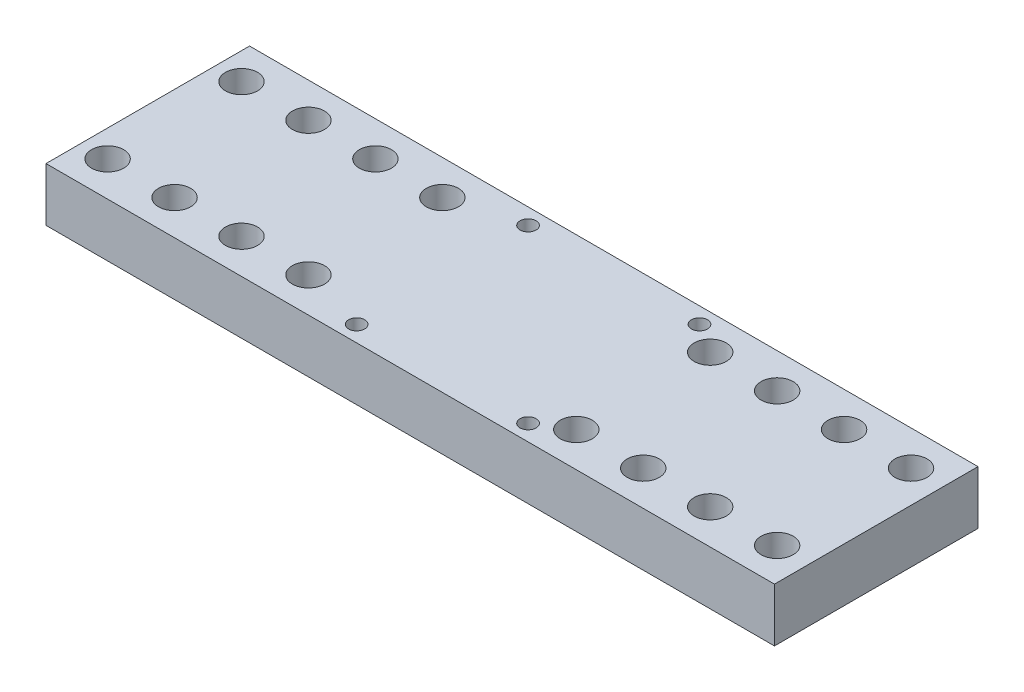
SolidWorks part; units mm, degrees
ref_plane "Front Plane" through (0, 0, 0) normal (0, 0, 1) x (1, 0, 0)
ref_plane "Top Plane" through (0, 0, 0) normal (0, 1, 0) x (1, 0, 0)
ref_plane "Right Plane" through (0, 0, 0) normal (1, 0, 0) x (0, 0, -1)
sketch "Sketch1" plane through (0, 0, 0) normal (0, 1, 0) x (1, 0, 0)
  line L1 (-70.9695, -35.3595) -> (65.0305, -35.3595)
  line L2 (-70.9695, -35.3595) -> (-70.9695, 2.6405)
  line L3 (-70.9695, 2.6405) -> (65.0305, 2.6405)
  line L4 (65.0305, -35.3595) -> (65.0305, 2.6405)
  line L5 (-15.9695, -0.3595) -> (16.0305, -0.3595) construction
  line L6 (-15.9695, -0.3595) -> (-15.9695, -32.3595) construction
  line L7 (-15.9695, -32.3595) -> (16.0305, -32.3595) construction
  line L8 (16.0305, -0.3595) -> (16.0305, -32.3595) construction
  line L9 (-65.9695, -3.8595) -> (-40.9695, -3.8595) construction
  line L10 (-65.9695, -3.8595) -> (-65.9695, -28.8595) construction
  line L11 (-65.9695, -28.8595) -> (-40.9695, -28.8595) construction
  line L12 (-40.9695, -3.8595) -> (-40.9695, -28.8595) construction
  circle A0 centre (-15.9695, -0.3595) radius 1.5
  circle A1 centre (16.0305, -0.3595) radius 1.5
  circle A2 centre (16.0305, -32.3595) radius 1.5
  circle A3 centre (-15.9695, -32.3595) radius 1.5
  circle A4 centre (-65.9695, -3.8595) radius 3
  circle A5 centre (-40.9695, -3.8595) radius 3
  circle A6 centre (-40.9695, -28.8595) radius 3
  circle A7 centre (-65.9695, -28.8595) radius 3
  circle A8 centre (-28.4695, -28.8595) radius 3
  circle A9 centre (-53.4695, -3.8595) radius 3
  circle A10 centre (-53.4695, -28.8595) radius 3
  circle A11 centre (-28.4695, -3.8595) radius 3
  circle A12 centre (34.0305, -3.8595) radius 3
  circle A13 centre (59.0305, -28.8595) radius 3
  circle A14 centre (59.0305, -3.8595) radius 3
  circle A15 centre (34.0305, -28.8595) radius 3
  circle A16 centre (21.5305, -28.8595) radius 3
  circle A17 centre (46.5305, -28.8595) radius 3
  circle A18 centre (21.5305, -3.8595) radius 3
  circle A19 centre (46.5305, -3.8595) radius 3
  point P20 (-15.9695, -16.3595)
  point P21 (-40.9695, -16.3595)
  dimension "D1" = 3
  dimension "D3" = 6
  dimension "D10" = 125
  dimension "D2" = 32
  dimension "D4" = 25
  dimension "D5" = 25
  dimension "D6" = 3
  dimension "D7" = 3
  dimension "D8" = 6
  dimension "D9" = 5
extrude "Boss-Extrude1" add sketch "Sketch1" along normal blind 10
